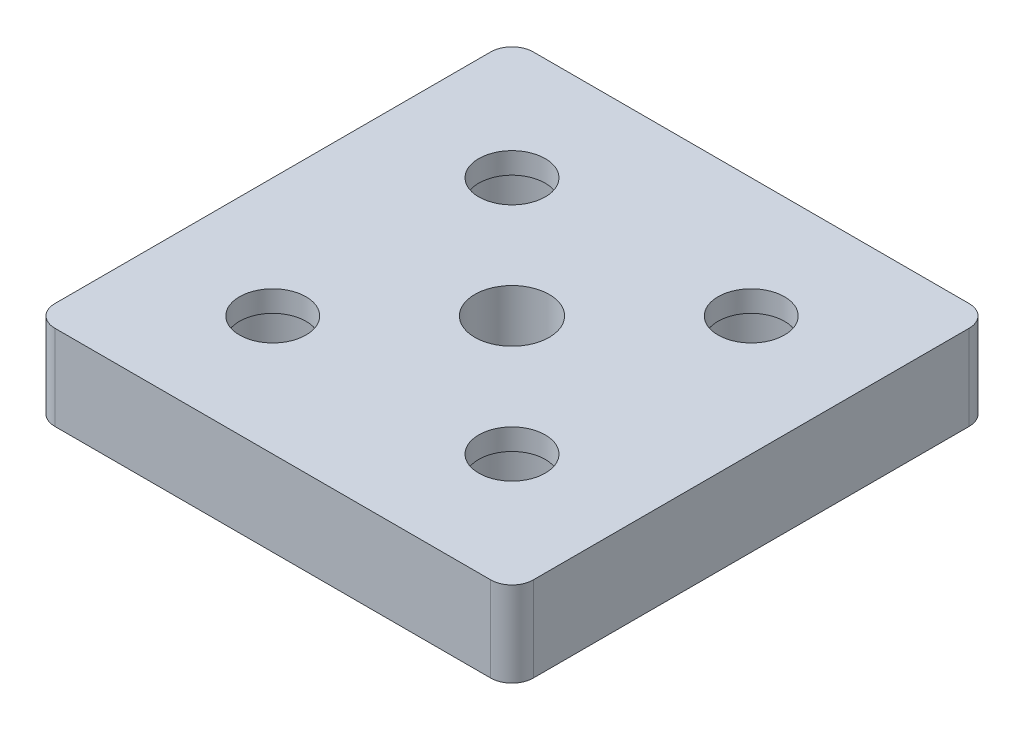
SolidWorks part; units mm, degrees
ref_plane "前视基准面" through (0, 0, 0) normal (0, 0, 1) x (1, 0, 0)
ref_plane "上视基准面" through (0, 0, 0) normal (0, 1, 0) x (1, 0, 0)
ref_plane "右视基准面" through (0, 0, 0) normal (1, 0, 0) x (0, 0, -1)
sketch "草图1" plane through (0, 0, 0) normal (0, 1, 0) x (1, 0, 0)
  line B0 (-41, 0) -> (41, 0)
  line B1 (45, 4) -> (45, 86)
  line B2 (41, 90) -> (-41, 90)
  line B3 (-45, 86) -> (-45, 4)
  arc B4 (41, 0) -> (45, 4) centre (41, 4) ccw
  arc B5 (45, 86) -> (41, 90) centre (41, 86) ccw
  arc B6 (-41, 90) -> (-45, 86) centre (-41, 86) ccw
  arc B7 (-45, 4) -> (-41, 0) centre (-41, 4) ccw
  circle B8 centre (22.5, 67.5) radius 6.25
  circle B9 centre (-22.5, 67.5) radius 6.25
  circle B10 centre (-22.5, 22.5) radius 6.25
  circle B11 centre (22.5, 22.5) radius 6.25
sketch_block_instance "A$C68FA715F-1"
sketch_block "A$C68FA715F"
extrude "凸台-拉伸1" add sketch "草图1" along normal blind 16
sketch "草图3" plane through (0, 0, 0) normal (0, -1, 0) x (1, 0, 0)
  circle A0 centre (22.5, -22.5) radius 9.25
  circle A1 centre (22.5, -67.5) radius 9.25
  circle A2 centre (-22.5, -67.5) radius 9.25
  circle A3 centre (-22.5, -22.5) radius 9.25
extrude "切除-拉伸1" cut sketch "草图3" against normal blind 12
sketch "草图4" plane through (0, 16, 0) normal (0, 1, 0) x (1, 0, 0)
  point P0 (0, 45)
hole_wizard "M16 螺纹孔1" positions "3D草图1" profile "草图5" tap size "M16" standard "Iso"
sketch3d "3D草图1"
  point P0 (0, 16, -45)
sketch "草图5" plane through (0, 16, -45) normal (1, 0, 0) x (0, 0, 1)
  line L0 (0, 0) -> (0, 42.206)
  line L1 (0, 42.206) -> (7, 38)
  line L2 (7, 38) -> (7, 0)
  line L5 (7, 0) -> (0, 0)
  line L10 (0, 42.206) -> (-7, 38) construction
  line L11 (0, -6.35) -> (0, 107.95) construction
  dimension "螺纹孔钻头直径" = 14
  dimension "螺纹孔钻头深度" = 38
  dimension "导头角度" = 118
cosmetic thread "孔螺蚊线1" parameters "D1"=16, "D2"=16
